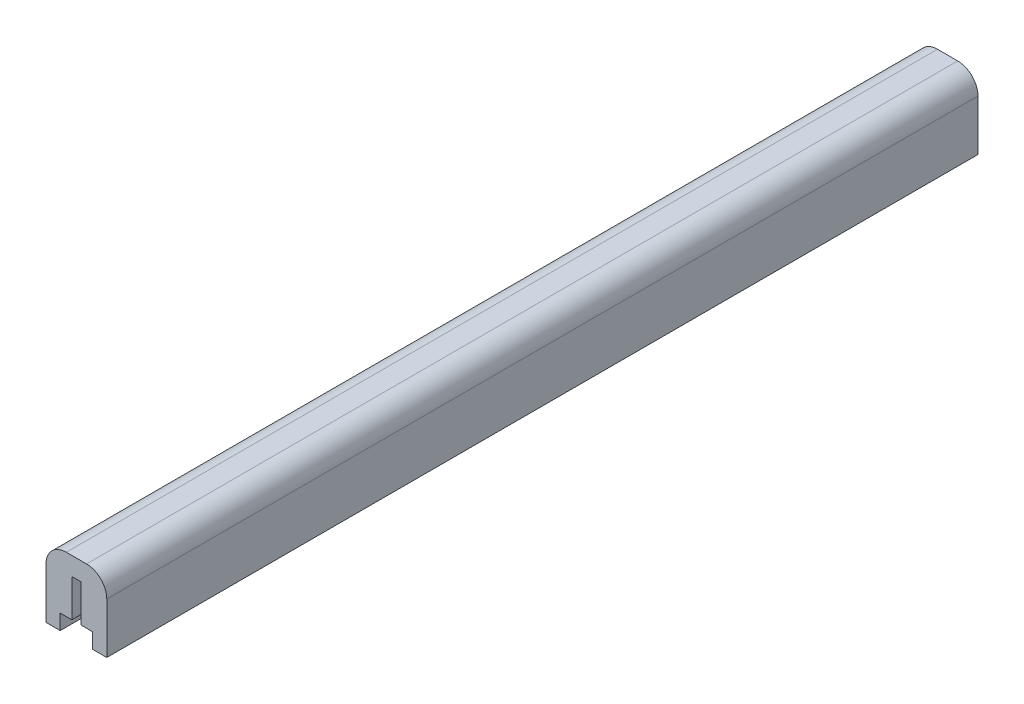
SolidWorks part; units mm, degrees
material "Pin"
ref_plane "Plan de face" through (0, 0, 0) normal (0, 0, 1) x (1, 0, 0)
ref_plane "Plan de dessus" through (0, 0, 0) normal (0, 1, 0) x (1, 0, 0)
ref_plane "Plan de droite" through (0, 0, 0) normal (1, 0, 0) x (0, 0, -1)
sketch "Esquisse2" plane through (0, 0, 0) normal (0, 0, 1) x (1, 0, 0)
  line L0 (-15, 0) -> (15, 0) construction
  line L1 (-15, 0) -> (-15, 25)
  line L2 (-5, 35) -> (5, 35)
  line L3 (15, 25) -> (15, 0)
  line L4 (-15, 0) -> (-8, 0)
  line L5 (-8, 0) -> (-8, 7.5)
  line L6 (-8, 7.5) -> (-2.25, 7.5)
  line L7 (-2.25, 7.5) -> (-2.25, 26)
  line L8 (-2.25, 26) -> (2.25, 26)
  line L9 (2.25, 26) -> (2.25, 7.5)
  line L10 (2.25, 7.5) -> (8, 7.5)
  line L11 (8, 7.5) -> (8, 0)
  line L12 (8, 0) -> (15, 0)
  line L13 (-8, 7.5) -> (8, 7.5) construction
  arc A0 (5, 35) -> (15, 25) centre (5, 25) cw
  arc A1 (-15, 25) -> (-5, 35) centre (-5, 25) cw
  point P3 (0, 0)
  point P15 (0, 26)
  point P19 (0, 7.5)
  dimension "D1" = 10
  dimension "D2" = 30
  dimension "D3" = 35
  dimension "D4" = 16
  dimension "D5" = 7.5
  dimension "D6" = 26
  dimension "D7" = 4.5
extrude "Boss.-Extru.1" add sketch "Esquisse2" along normal blind 430
